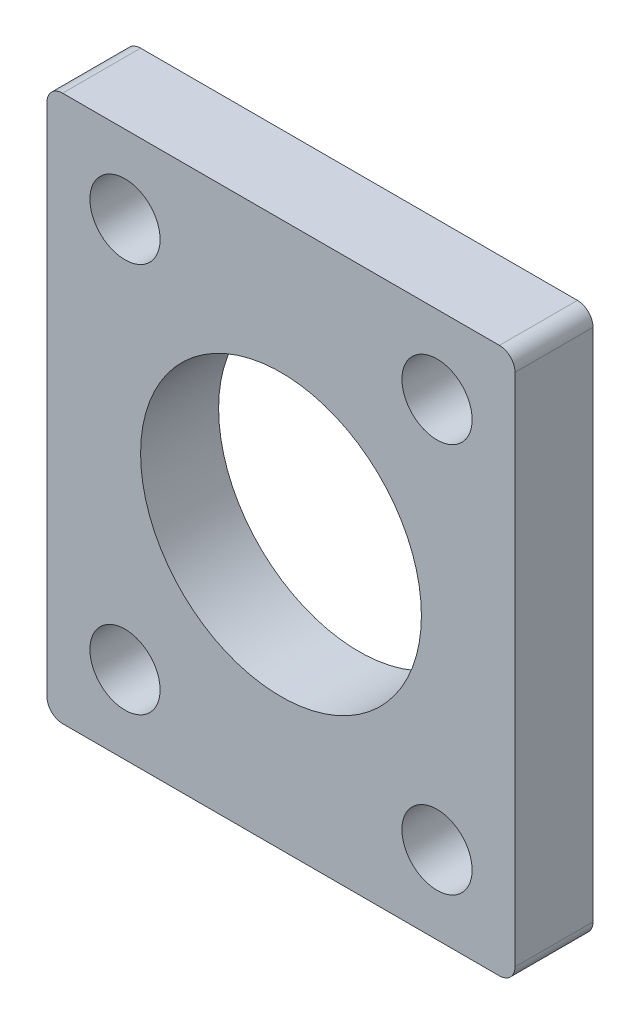
SolidWorks part; units mm, degrees
ref_plane "Front Plane" through (0, 0, 0) normal (0, 0, 1) x (1, 0, 0)
ref_plane "Top Plane" through (0, 0, 0) normal (0, 1, 0) x (1, 0, 0)
ref_plane "Right Plane" through (0, 0, 0) normal (1, 0, 0) x (0, 0, -1)
sketch "Sketch1" plane through (0, 0, 0) normal (0, 0, 1) x (1, 0, 0)
  line L0 (30, 0) -> (-30, 0) construction
  line L1 (-30, -35) -> (30, -35)
  line L2 (-30, -35) -> (-30, 35)
  line L3 (-30, 35) -> (30, 35)
  line L4 (30, -35) -> (30, 35)
  line L5 (-30, -35) -> (30, 35) construction
  line L6 (-30, 35) -> (30, -35) construction
  circle A1 centre (0, 0) radius 18
  dimension "D1" = 70
  dimension "D2" = 36
  dimension "D3" = 60
extrude "Boss-Extrude1" add sketch "Sketch1" along normal blind 10
fillet "Fillet1" radius 2 4 edges at (-30, 35, 5) (30, 35, 5) (30, -35, 5) (-30, -35, 5)
extrude "Cut-Extrude2" cut sketch "Sketch3" along normal blind 100
sketch "Sketch3" plane through (-387.4722, 43.5753, 11) normal (0, 0, -1) x (-1, 0, 0)
  line L0 (-387.4722, -18.5753) -> (-387.4722, -68.5753) construction
  line L1 (-407.4722, -18.5753) -> (-367.4722, -18.5753) construction
  line L2 (-407.4722, -18.5753) -> (-407.4722, -68.5753) construction
  line L3 (-407.4722, -68.5753) -> (-367.4722, -68.5753) construction
  line L4 (-367.4722, -18.5753) -> (-367.4722, -68.5753) construction
  line L5 (-367.4722, -43.5753) -> (-407.4722, -43.5753) construction
  circle A4 centre (-407.4722, -68.5753) radius 4.5
  circle A5 centre (-367.4722, -68.5753) radius 4.5
  circle A6 centre (-367.4722, -18.5753) radius 4.5
  circle A7 centre (-407.4722, -18.5753) radius 4.5
  point P12 (-387.4722, -43.5753)
  dimension "D1" = 9
sketch "Sketch4" plane through (0, 0, 0) normal (0, 0, -1) x (-1, 0, 0)
  circle A0 centre (-20, 25) radius 8 construction
  circle A1 centre (-20, 25) radius 10 construction
  dimension "D1" = 16
  dimension "D2" = 20
